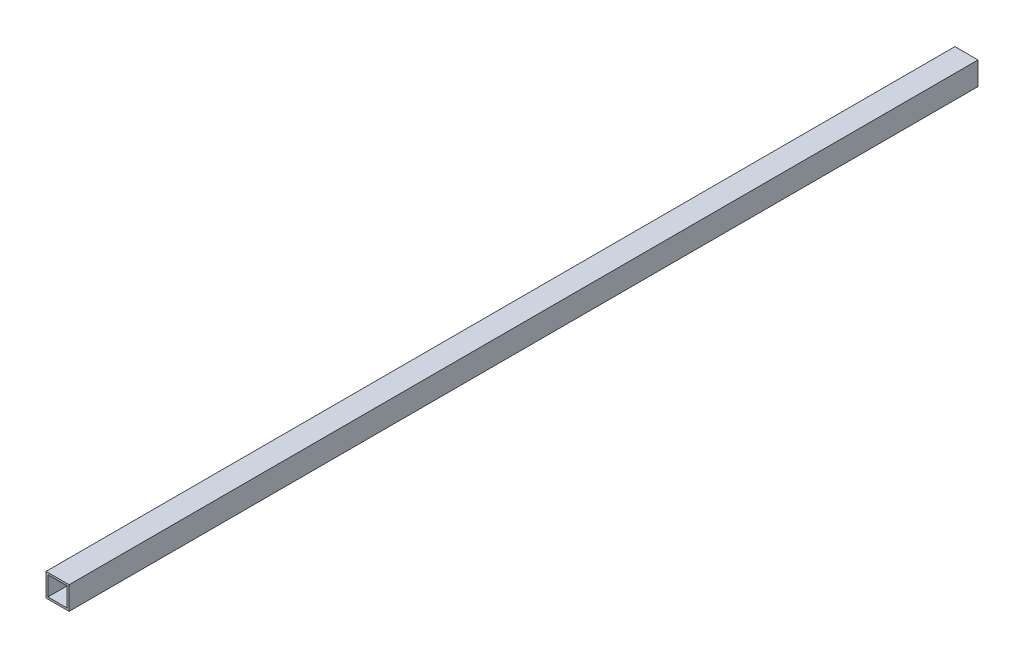
SolidWorks part; units mm, degrees
ref_plane "Front Plane" through (0, 0, 0) normal (0, 0, 1) x (1, 0, 0)
ref_plane "Top Plane" through (0, 0, 0) normal (0, 1, 0) x (1, 0, 0)
ref_plane "Right Plane" through (0, 0, 0) normal (1, 0, 0) x (0, 0, -1)
sketch "Sketch2" plane through (0, 0, 0) normal (0, 0, 1) x (1, 0, 0)
  line L0 (-15.875, 15.875) -> (-19.05, 15.875)
  line L1 (-19.05, 19.05) -> (19.05, 19.05)
  line L2 (-19.05, 19.05) -> (-19.05, 15.875)
  line L3 (-19.05, -19.05) -> (19.05, -19.05)
  line L4 (19.05, 19.05) -> (19.05, -19.05)
  line L5 (-19.05, 19.05) -> (19.05, -19.05) construction
  line L6 (-19.05, -19.05) -> (19.05, 19.05) construction
  line L7 (-15.875, 15.875) -> (15.875, 15.875)
  line L8 (-15.875, 15.875) -> (-15.875, -15.875)
  line L9 (-15.875, -15.875) -> (15.875, -15.875)
  line L10 (15.875, 15.875) -> (15.875, -15.875)
  line L11 (-15.875, 15.875) -> (15.875, -15.875) construction
  line L12 (-15.875, -15.875) -> (15.875, 15.875) construction
  line L13 (-15.875, -15.875) -> (-19.05, -15.875)
  line L14 (-19.05, -15.875) -> (-19.05, -19.05)
  point P0 (0, 0)
  point P6 (0, 0)
  dimension "D1" = 38.1
  dimension "D2" = 38.1
  dimension "D3" = 31.75
  dimension "D4" = 31.75
extrude "Boss-Extrude1" add sketch "Sketch2" along normal blind 609.6 contours L13 L14 L3 L4 L1 L2 L0 L7 L10 L9
sketch "Sketch3" plane through (0, -19.05, 0) normal (0, -1, 0) x (1, 0, 0)
  line L0 (0, 609.6) -> (0, 589.6) construction
  line L1 (-19.05, 609.6) -> (19.05, 609.6) construction
  line L2 (0, 589.6) -> (0, 574.6) construction
  line L3 (0, 574.6) -> (0, 539.6) construction
  line L4 (0, 539.6) -> (0, 504.6) construction
  line L5 (0, 504.6) -> (0, 469.6) construction
  circle A0 centre (0, 574.6) radius 4.5
  circle A1 centre (0, 539.6) radius 4.5
  circle A3 centre (0, 469.6) radius 4.5
  circle A4 centre (0, 504.6) radius 4.5
  dimension "D6" = 9
  dimension "D7" = 9
  dimension "D8" = 9
  dimension "D9" = 9
  dimension "D1" = 20
  dimension "D2" = 15
  dimension "D3" = 35
  dimension "D4" = 35
  dimension "D5" = 35
extrude "Cut-Extrude1" cut sketch "Sketch3" against normal blind 10
sketch "Sketch4" plane through (0, 19.05, 0) normal (0, 1, 0) x (1, 0, 0)
  line L0 (0, -609.6) -> (0, -504.6) construction
  line L1 (-19.05, -609.6) -> (19.05, -609.6) construction
  line L2 (0, -504.6) -> (0, -204.6) construction
  line L3 (0, -204.6) -> (19.05, -204.6) construction
  line L4 (19.05, -609.6) -> (19.05, 0) construction
  line L5 (19.05, -176.26) -> (19.05, -232.94) construction
  line L6 (19.05, -176.26) -> (19.05, -189.8399)
  line L7 (19.05, -189.8399) -> (1.2013, -189.8399)
  line L8 (19.05, -189.8399) -> (19.05, -218.771)
  line L9 (19.05, -218.771) -> (8.2864, -218.771)
  circle A0 centre (1.2013, -189.8399) radius 2.04
  circle A1 centre (8.2864, -218.771) radius 2.04
  dimension "D8" = 4.08
  dimension "D9" = 4.08
  dimension "D1" = 105
  dimension "D2" = 300
  dimension "D3" = 28.34
  dimension "D4" = 13.5799
  dimension "D5" = 17.8487
  dimension "D6" = 28.9311
  dimension "D7" = 10.7636
sketch "Sketch5" plane through (19.05, 0, 0) normal (1, 0, 0) x (0, 0, -1)
  line L0 (-609.6, 19.05) -> (-609.6, 8.89) construction
  line L1 (-609.6, 19.05) -> (-609.6, -19.05) construction
  line L2 (-609.6, 8.89) -> (-504.6, 8.89) construction
  line L3 (-504.6, 8.89) -> (-204.6, 8.89) construction
  line L4 (-204.6, 8.89) -> (-232.94, 8.89) construction
  line L5 (-204.6, 8.89) -> (-176.26, 8.89)
  line L6 (-176.26, 8.89) -> (-189.84, 8.89)
  line L7 (-176.26, 8.89) -> (-176.26, -8.96)
  line L8 (-176.26, -8.96) -> (-189.84, -8.96)
  line L9 (-189.84, 8.89) -> (-218.77, 8.89)
  line L10 (-218.77, 8.89) -> (-218.77, -1.87)
  circle A0 centre (-218.77, -1.87) radius 2.03
  circle A1 centre (-189.84, -8.96) radius 2.03
  dimension "D10" = 4.06
  dimension "D11" = 4.06
  dimension "D1" = 10.16
  dimension "D2" = 105
  dimension "D3" = 300
  dimension "D4" = 28.34
  dimension "D5" = 28.34
  dimension "D6" = 13.58
  dimension "D7" = 17.85
  dimension "D8" = 28.93
  dimension "D9" = 10.76
sketch "Sketch6" plane through (0, 0, 0) normal (0, 0, -1) x (-1, 0, 0)
  line L1 (19.05, 19.05) -> (-15.875, 19.05)
  line L2 (19.05, 19.05) -> (19.05, 15.875)
  line L3 (19.05, 15.875) -> (-15.875, 15.875)
  line L4 (-15.875, 19.05) -> (-15.875, 15.875)
  line L5 (-19.05, 19.05) -> (-15.875, 19.05)
  line L6 (-19.05, 19.05) -> (-19.05, -15.875)
  line L7 (-19.05, -15.875) -> (-15.875, -15.875)
  line L8 (-15.875, 19.05) -> (-15.875, -15.875)
  line L9 (-19.05, -15.875) -> (19.05, -15.875)
  line L10 (-19.05, -15.875) -> (-19.05, -19.05)
  line L11 (-19.05, -19.05) -> (19.05, -19.05)
  line L12 (19.05, -15.875) -> (19.05, -19.05)
  line M1 (19.05, -15.875) -> (-15.875, -15.875)
  line M2 (-15.875, -15.875) -> (-15.875, 15.875)
  line M3 (-15.875, 15.875) -> (19.05, 15.875)
  line M4 (19.05, 15.875) -> (19.05, 19.05)
  line M5 (19.05, 19.05) -> (-19.05, 19.05)
  line M6 (-19.05, 19.05) -> (-19.05, -19.05)
  line M7 (-19.05, -19.05) -> (19.05, -19.05)
  line M8 (19.05, -19.05) -> (19.05, -15.875)
extrude "Boss-Extrude2" add sketch "Sketch6" along normal blind 890.4 contours L7 M6 M7 M8 M1 | L7 L4 M6 M2 M5 | L4 M5 M3 M4
sketch "Sketch7" plane through (0, 0, 609.6) normal (0, 0, 1) x (1, 0, 0)
  line L0 (-19.05, -19.05) -> (19.05, -19.05) construction
  line L1 (-19.05, 19.05) -> (-15.875, 19.05)
  line L2 (-19.05, 19.05) -> (-19.05, -19.05)
  line L3 (-19.05, -19.05) -> (-15.875, -19.05)
  line L4 (-15.875, 19.05) -> (-15.875, -19.05)
  dimension "D1" = 3.175
extrude "Boss-Extrude3" add sketch "Sketch7" against normal blind 1500
ref_plane "Plane1" through (0, 0, 0) normal (1, 0, 0) x (0, 0, -1)
sketch "Sketch8" plane through (0, 0, 0) normal (1, 0, 0) x (0, 0, -1)
  line L0 (-609.6, 0) -> (890.4, 0) construction
sketch "Sketch9" plane through (19.05, 0, 0) normal (1, 0, 0) x (0, 0, -1)
  line L1 (-609.6, 19.05) -> (890.4, 19.05)
  line L2 (-609.6, 19.05) -> (-609.6, -19.05)
  line L3 (-609.6, -19.05) -> (890.4, -19.05)
  line L4 (890.4, 19.05) -> (890.4, -19.05)
